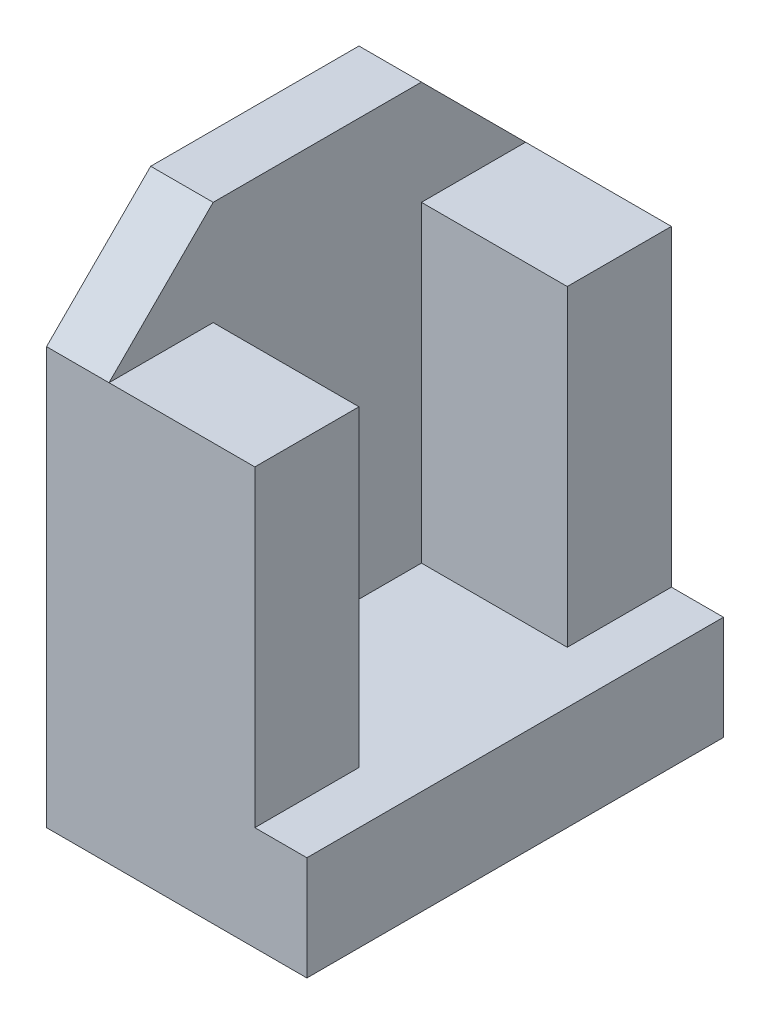
SolidWorks part; units mm, degrees
ref_plane "Front Plane" through (0, 0, 0) normal (0, 0, 1) x (1, 0, 0)
ref_plane "Top Plane" through (0, 0, 0) normal (0, 1, 0) x (1, 0, 0)
ref_plane "Right Plane" through (0, 0, 0) normal (1, 0, 0) x (0, 0, -1)
sketch "Sketch1" plane through (0, 0, 0) normal (0, 0, 1) x (1, 0, 0)
  line L0 (0, 0) -> (25000, 0)
  line L1 (25000, 0) -> (25000, 10000)
  line L2 (25000, 10000) -> (6000, 10000)
  line L3 (6000, 10000) -> (6000, 50000)
  line L4 (6000, 50000) -> (0, 50000)
  line L5 (0, 50000) -> (0, 0)
  line L6 (0, 0) -> (-856.0734, 0)
  dimension "D1" = 25000
  dimension "D2" = 50000
  dimension "D3" = 6000
  dimension "D4" = 10000
extrude "Boss-Extrude1" add sketch "Sketch1" against normal blind 40000 contours L4 L5 L0 L1 L2 L3
sketch "Sketch2" plane through (0, 0, 0) normal (-1, 0, 0) x (0, 0, 1)
  line L0 (-20000, 56912.0408) -> (-20000, -5303.0303) construction
  line L1 (-40000, 50000) -> (-30000, 50000)
  line L2 (-40000, 50000) -> (0, 50000) construction
  line L3 (-30000, 50000) -> (-40000, 40000)
  line L4 (-40000, 50000) -> (-40000, 0) construction
  line L5 (-40000, 40000) -> (-40000, 50000)
  line L6 (-10000, 50000) -> (0, 50000)
  line L7 (0, 50000) -> (0, 40000)
  line L8 (0, 50000) -> (0, 0) construction
  line L9 (0, 40000) -> (-10000, 50000)
  dimension "D1" = 10000
  dimension "D2" = 10000
  dimension "D3" = 10000
  dimension "D4" = 10000
extrude "Cut-Extrude1" cut sketch "Sketch2" against normal blind 6000
sketch "Sketch3" plane through (6000, 0, 0) normal (1, 0, 0) x (0, 0, -1)
  line L1 (0, 10000) -> (10000, 10000)
  line L2 (0, 10000) -> (0, 40000)
  line L3 (0, 40000) -> (10000, 40000)
  line L4 (10000, 10000) -> (10000, 40000)
  line L5 (40000, 10000) -> (30000, 10000)
  line L6 (40000, 10000) -> (40000, 40000)
  line L7 (40000, 40000) -> (30000, 40000)
  line L8 (30000, 10000) -> (30000, 40000)
  point P10 (0, 0)
  point P12 (0, 0)
  point P14 (0, 0)
  dimension "D1" = 10000
  dimension "D2" = 10000
extrude "Boss-Extrude2" add sketch "Sketch3" along normal blind 14000
